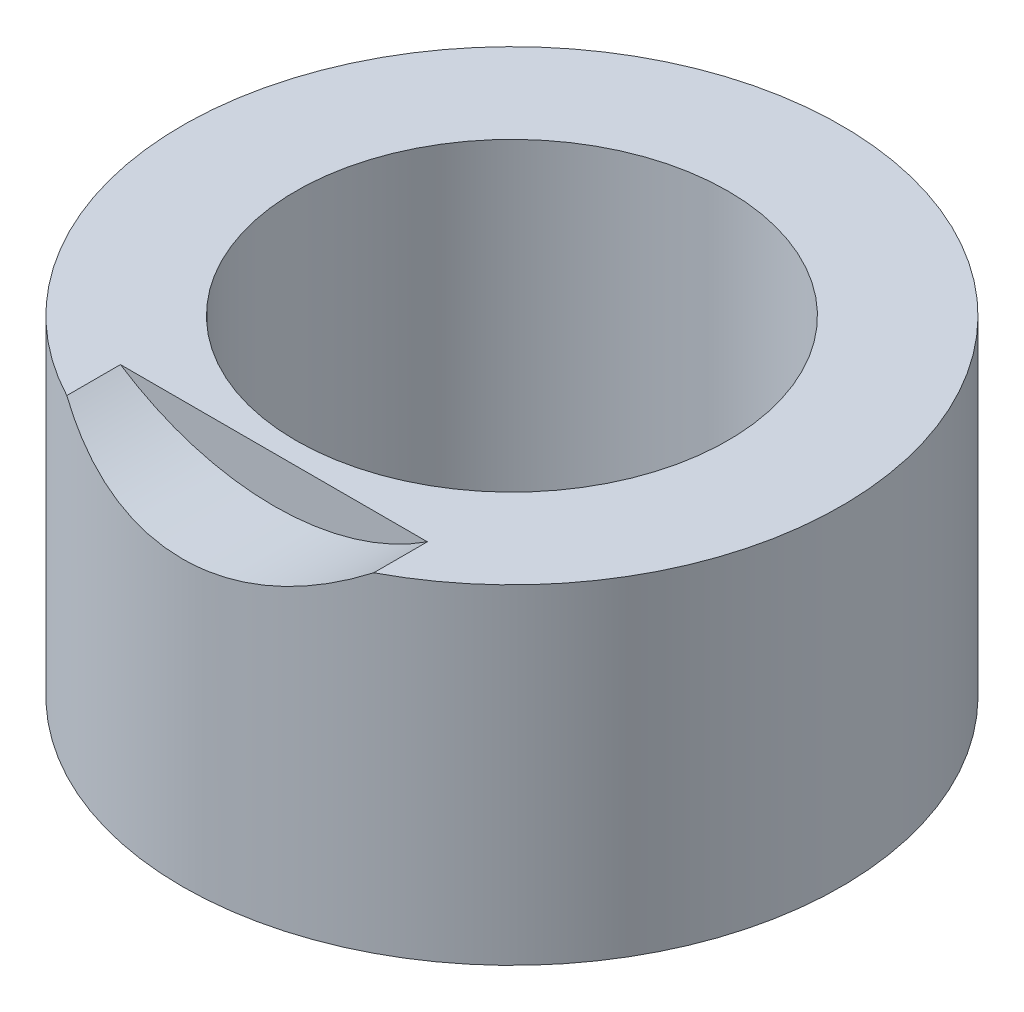
SolidWorks part; units mm, degrees
material "OMD-98"
ref_plane "Front Plane" through (0, 0, 0) normal (0, 0, 1) x (1, 0, 0)
ref_plane "Top Plane" through (0, 0, 0) normal (0, 1, 0) x (1, 0, 0)
ref_plane "Right Plane" through (0, 0, 0) normal (1, 0, 0) x (0, 0, -1)
sketch "Sketch1" plane through (0, 0, 0) normal (0, 1, 0) x (1, 0, 0)
  circle A0 centre (0, 0) radius 9
  circle A1 centre (0, 0) radius 5.9
  dimension "D1" = 18
  dimension "D2" = 11.8
extrude "Boss-Extrude1" add sketch "Sketch1" against normal blind 23.8
sketch "Sketch3" plane through (0, 0, 0) normal (0, 0, 1) x (1, 0, 0)
  line L1 (5.9, 0) -> (-5.9, 0) construction
  circle A0 centre (0, -8.4) radius 7.65
  dimension "D1" = 15.3
  dimension "D2" = 8.4
extrude "Cut-Extrude5" cut sketch "Sketch3" along normal through all from offset 6.5
sketch "Sketch6" plane through (0, 0, 6.5) normal (0, 0, 1) x (1, 0, 0)
  line L0 (-6.2249, -23.8) -> (6.2249, -23.8) construction
  line L1 (6.2249, 0) -> (6.2249, -23.8) construction
  circle A0 centre (0.1455, -8.4) radius 5.5
  dimension "D1" = 11
  dimension "D2" = 15.4
  dimension "D3" = 6.0795
extrude "Cut-Extrude6" cut sketch "Sketch6" against normal blind 7 and the other way through all
ref_plane "Plane1" through (0, -14.8, 0) normal (0, -1, 0) x (-1, 0, 0)
sketch "Sketch7" plane through (0, -14.8, 0) normal (0, -1, 0) x (-1, 0, 0)
  circle A0 centre (0, 0) radius 13.4843
extrude "Cut-Extrude7" cut sketch "Sketch7" against normal through all
